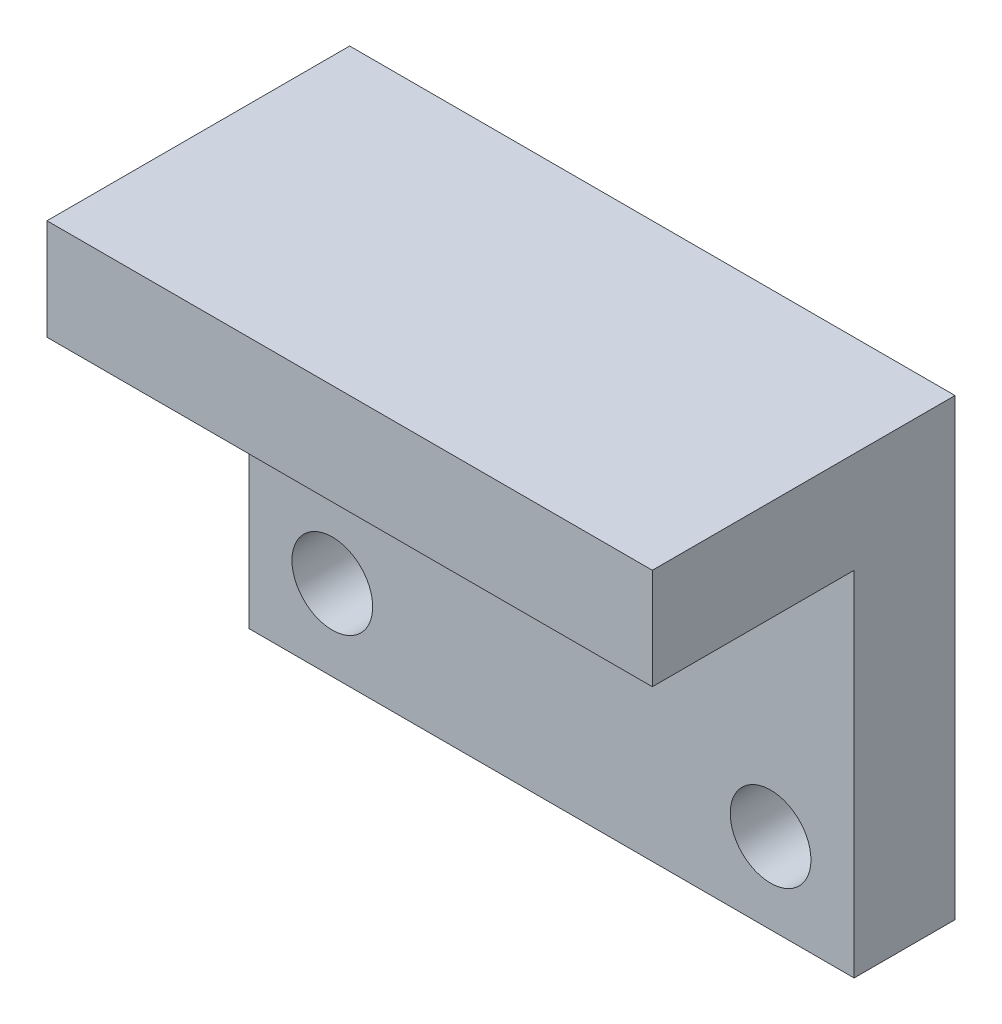
SolidWorks part; units mm, degrees
ref_plane "Front Plane" through (0, 0, 0) normal (0, 0, 1) x (1, 0, 0)
ref_plane "Top Plane" through (0, 0, 0) normal (0, 1, 0) x (1, 0, 0)
ref_plane "Right Plane" through (0, 0, 0) normal (1, 0, 0) x (0, 0, -1)
sketch "Sketch4" plane through (0, 0, 0) normal (0, 0, 1) x (1, 0, 0)
  line L0 (0, -15.2143) -> (0, 15.3214) construction
  line L1 (-15, 10) -> (15, 10)
  line L2 (-15, 10) -> (-15, -7.5)
  line L3 (-15, -7.5) -> (15, -7.5)
  line L4 (15, 10) -> (15, -7.5)
  circle A0 centre (10.86, -3.5) radius 2
  circle A1 centre (-10.86, -3.5) radius 2
  point P0 (0, 0)
  dimension "D3" = 4
  dimension "D4" = 4.14
  dimension "D5" = 4
  dimension "D1" = 30
  dimension "D2" = 17.5
extrude "Boss-Extrude2" add sketch "Sketch4" along normal blind 5
sketch "Sketch5" plane through (0, 0, 0) normal (0, 0, 1) x (1, 0, 0)
  line L0 (15, 10) -> (15, 15)
  line L1 (15, 10) -> (-15, 10)
  line L2 (-15, 10) -> (-15, 15)
  line L3 (-15, 15) -> (15, 15)
  dimension "D1" = 5
extrude "Boss-Extrude3" add sketch "Sketch5" along normal blind 15
